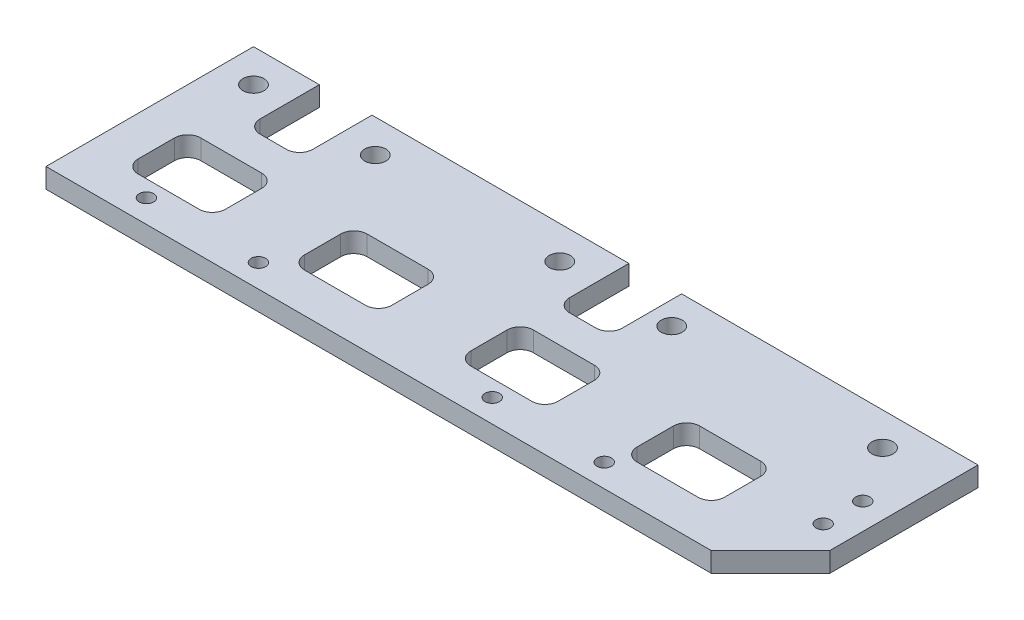
SolidWorks part; units mm, degrees
ref_plane "前视基准面" through (0, 0, 0) normal (0, 0, 1) x (1, 0, 0)
ref_plane "上视基准面" through (0, 0, 0) normal (0, 1, 0) x (1, 0, 0)
ref_plane "右视基准面" through (0, 0, 0) normal (1, 0, 0) x (0, 0, -1)
sketch "Sketch1" plane through (0, 0, 0) normal (0, 1, 0) x (1, 0, 0)
  line L0 (30.9082, 164.1303) -> (131.9082, 164.1303)
  line L1 (30.9082, 164.1303) -> (30.9082, 195.6303)
  line L2 (40.9082, 195.6303) -> (30.9082, 195.6303)
  line L3 (40.9082, 184.6303) -> (40.9082, 195.6303)
  line L4 (48.9082, 184.6303) -> (40.9082, 184.6303)
  line L5 (48.9082, 195.6303) -> (48.9082, 184.6303)
  line L6 (87.9082, 195.6303) -> (48.9082, 195.6303)
  line L7 (87.9082, 184.6303) -> (87.9082, 195.6303)
  line L8 (95.9082, 184.6303) -> (87.9082, 184.6303)
  line L9 (95.9082, 195.6303) -> (95.9082, 184.6303)
  line L10 (140.9082, 195.6303) -> (95.9082, 195.6303)
  line L11 (140.9082, 173.1303) -> (140.9082, 195.6303)
  line L12 (131.9082, 164.1303) -> (140.9082, 173.1303)
  line L13 (112.6582, 170.1303) -> (125.9082, 170.1303)
  line L14 (125.9082, 170.1303) -> (125.9082, 179.6303)
  line L15 (112.6582, 179.6303) -> (125.9082, 179.6303)
  line L16 (112.6582, 170.1303) -> (112.6582, 179.6303)
  line L17 (87.4082, 170.1303) -> (100.6582, 170.1303)
  line L18 (100.6582, 170.1303) -> (100.6582, 179.6303)
  line L19 (87.4082, 179.6303) -> (100.6582, 179.6303)
  line L20 (87.4082, 170.1303) -> (87.4082, 179.6303)
  line L21 (50.1582, 170.1303) -> (50.1582, 179.6303)
  line L22 (50.1582, 179.6303) -> (36.9082, 179.6303)
  line L23 (36.9082, 170.1303) -> (36.9082, 179.6303)
  line L24 (50.1582, 170.1303) -> (36.9082, 170.1303)
  line L25 (75.4082, 170.1303) -> (75.4082, 179.6303)
  line L26 (75.4082, 179.6303) -> (62.1582, 179.6303)
  line L27 (75.4082, 170.1303) -> (62.1582, 170.1303)
  line L28 (62.1582, 170.1303) -> (62.1582, 179.6303)
  circle A0 centre (131.4082, 190.6303) radius 1.6
  circle A1 centre (99.4082, 190.6303) radius 1.6
  circle A2 centre (82.4082, 190.6303) radius 1.6
  circle A3 centre (54.4082, 190.6303) radius 1.6
  circle A4 centre (35.9082, 190.6303) radius 1.6
  circle A5 centre (112.1582, 167.6303) radius 1.1
  circle A6 centre (95.1582, 167.6303) radius 1.1
  circle A7 centre (59.6582, 167.6303) radius 1.1
  circle A8 centre (42.6582, 167.6303) radius 1.1
  circle A9 centre (136.9082, 176.1303) radius 1.1
  circle A10 centre (136.9082, 182.1303) radius 1.1
extrude "Extrude1" add sketch "Sketch1" along normal blind 3
fillet "圆角1" radius 2 20 edges at (125.9082, 1.5, -170.1303) (112.6582, 1.5, -170.1303) (112.6582, 1.5, -179.6303) (125.9082, 1.5, -179.6303) (100.6582, 1.5, -179.6303) (100.6582, 1.5, -170.1303) (87.4082, 1.5, -179.6303) (87.4082, 1.5, -170.1303) (62.1582, 1.5, -170.1303) (62.1582, 1.5, -179.6303) (75.4082, 1.5, -179.6303) (75.4082, 1.5, -170.1303) (50.1582, 1.5, -170.1303) (36.9082, 1.5, -170.1303) (36.9082, 1.5, -179.6303) (50.1582, 1.5, -179.6303) (40.9082, 1.5, -184.6303) (48.9082, 1.5, -184.6303) (87.9082, 1.5, -184.6303) (95.9082, 1.5, -184.6303)
